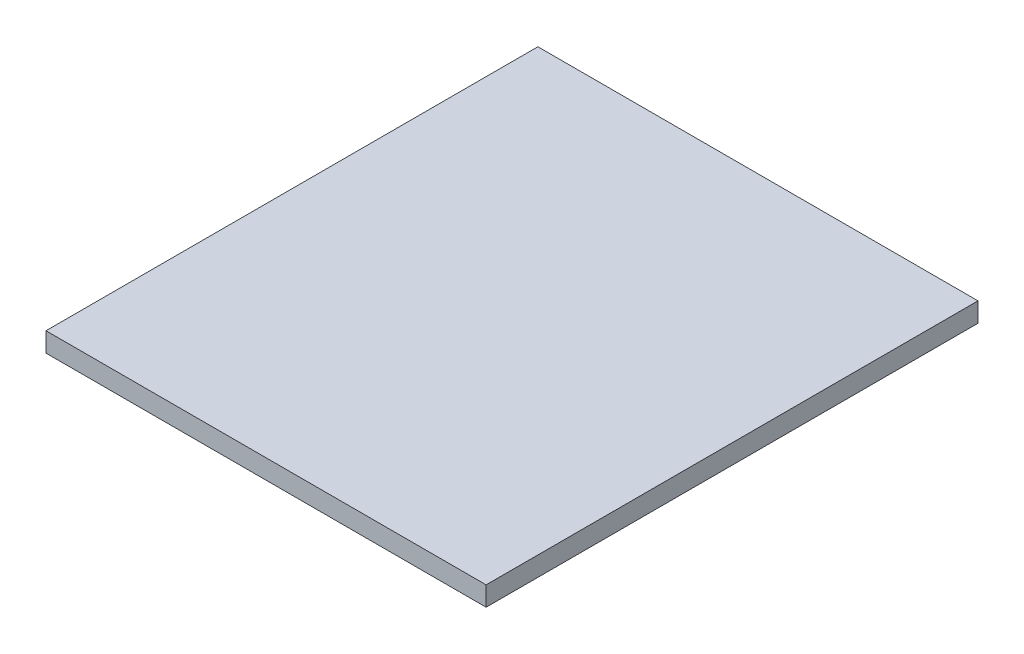
SolidWorks part; units mm, degrees
ref_plane "Front Plane" through (0, 0, 0) normal (0, 0, 1) x (1, 0, 0)
ref_plane "Top Plane" through (0, 0, 0) normal (0, 1, 0) x (1, 0, 0)
ref_plane "Right Plane" through (0, 0, 0) normal (1, 0, 0) x (0, 0, -1)
sketch "Sketch1" plane through (0, 0, 0) normal (0, 1, 0) x (1, 0, 0)
  line L1 (-340, 380) -> (340, 380)
  line L2 (-340, 380) -> (-340, -380)
  line L3 (-340, -380) -> (340, -380)
  line L4 (340, 380) -> (340, -380)
  line L5 (-340, 380) -> (340, -380) construction
  line L6 (-340, -380) -> (340, 380) construction
  point P0 (0, 0)
  dimension "D1" = 760
  dimension "D2" = 680
extrude "Boss-Extrude1" add sketch "Sketch1" along normal blind 30
